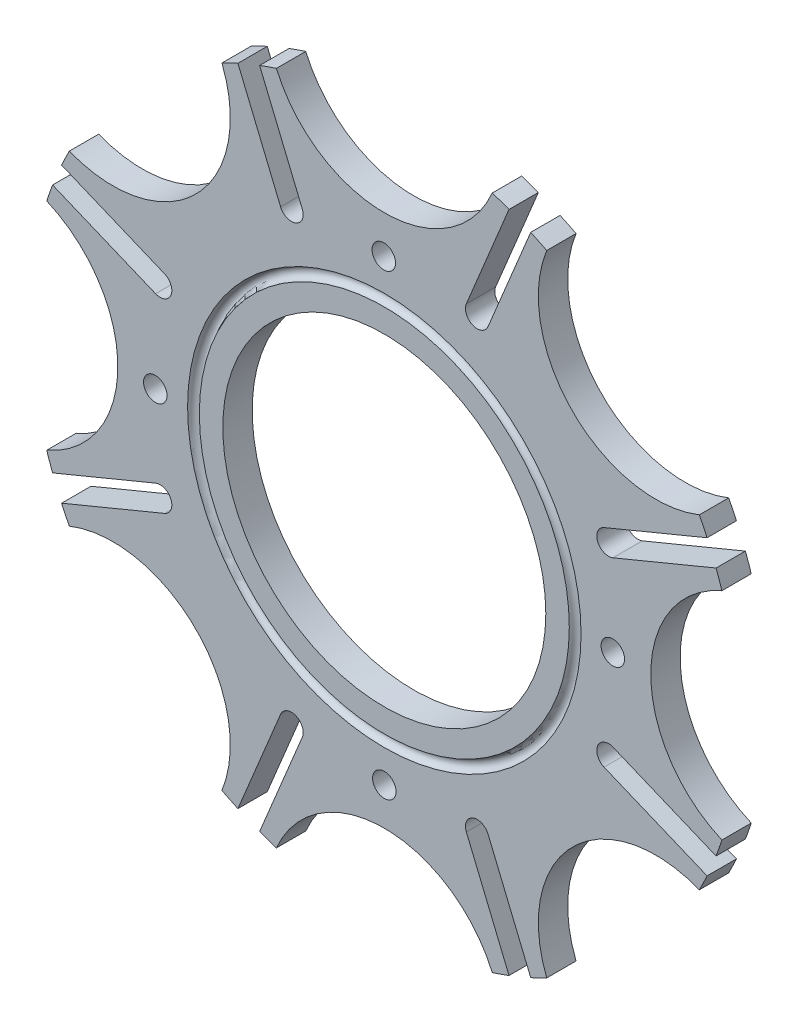
SolidWorks part; units mm, degrees
ref_plane "Front Plane" through (0, 0, 0) normal (0, 0, 1) x (1, 0, 0)
ref_plane "Top Plane" through (0, 0, 0) normal (0, 1, 0) x (1, 0, 0)
ref_plane "Right Plane" through (0, 0, 0) normal (1, 0, 0) x (0, 0, -1)
sketch "Sketch1" plane through (0, 0, 0) normal (0, 0, 1) x (1, 0, 0)
  arc A0 (-42.4681, -112.9795) -> (-36.7553, -114.965) centre (0, 0) ccw
  arc A1 (36.7553, -114.965) -> (42.4681, -112.9795) centre (0, 0) ccw
  arc A2 (49.8591, -109.918) -> (55.3026, -107.2825) centre (0, 0) ccw
  arc A3 (107.2825, -55.3026) -> (109.918, -49.8591) centre (0, 0) ccw
  arc A4 (112.9795, -42.4681) -> (114.965, -36.7553) centre (0, 0) ccw
  arc A5 (114.965, 36.7553) -> (112.9795, 42.4681) centre (0, 0) ccw
  arc A6 (109.918, 49.8591) -> (107.2825, 55.3026) centre (0, 0) ccw
  arc A7 (55.3026, 107.2825) -> (49.8591, 109.918) centre (0, 0) ccw
  arc A8 (42.4681, 112.9795) -> (36.7553, 114.965) centre (0, 0) ccw
  arc A9 (-36.7553, 114.965) -> (-42.4681, 112.9795) centre (0, 0) ccw
  arc A10 (-49.8591, 109.918) -> (-55.3026, 107.2825) centre (0, 0) ccw
  arc A11 (-107.2825, 55.3026) -> (-109.918, 49.8591) centre (0, 0) ccw
  arc A12 (-112.9795, 42.4681) -> (-114.965, 36.7553) centre (0, 0) ccw
  arc A13 (-114.965, -36.7553) -> (-112.9795, -42.4681) centre (0, 0) ccw
  arc A14 (-109.918, -49.8591) -> (-107.2825, -55.3026) centre (0, 0) ccw
  arc A15 (-55.3026, -107.2825) -> (-49.8591, -109.918) centre (0, 0) ccw
  circle A16 centre (0, 0) radius 65 construction
  circle A17 centre (0, 0) radius 62 construction
  circle A18 centre (0, 0) radius 55
  circle A19 centre (0, -0.09) radius 120.7776 construction
  line B0 (0, 0) -> (-46.2257, -111.5988) construction
  line B1 (-27.9356, -77.895) -> (-42.4681, -112.9795)
  line B2 (-35.3266, -74.8336) -> (-49.8591, -109.918)
  line B3 (0, 0) -> (46.2257, -111.5988) construction
  line B4 (35.3266, -74.8336) -> (49.8591, -109.918)
  line B5 (27.9356, -77.895) -> (42.4681, -112.9795)
  line B6 (0, 0) -> (111.5988, -46.2257) construction
  line B7 (77.895, -27.9356) -> (112.9795, -42.4681)
  line B8 (74.8336, -35.3266) -> (109.918, -49.8591)
  line B9 (0, 0) -> (111.5988, 46.2257) construction
  line B10 (74.8336, 35.3266) -> (109.918, 49.8591)
  line B11 (77.895, 27.9356) -> (112.9795, 42.4681)
  line B12 (0, 0) -> (46.2257, 111.5988) construction
  line B13 (27.9356, 77.895) -> (42.4681, 112.9795)
  line B14 (35.3266, 74.8336) -> (49.8591, 109.918)
  line B15 (0, 0) -> (-46.2257, 111.5988) construction
  line B16 (-35.3266, 74.8336) -> (-49.8591, 109.918)
  line B17 (-27.9356, 77.895) -> (-42.4681, 112.9795)
  line B18 (0, 0) -> (-111.5988, 46.2257) construction
  line B19 (-77.895, 27.9356) -> (-112.9795, 42.4681)
  line B20 (-74.8336, 35.3266) -> (-109.918, 49.8591)
  line B21 (0, 0) -> (-111.5988, -46.2257) construction
  line B22 (-74.8336, -35.3266) -> (-109.918, -49.8591)
  line B23 (-77.895, -27.9356) -> (-112.9795, -42.4681)
  arc B24 (-27.9356, -77.895) -> (-35.3266, -74.8336) centre (-31.6311, -76.3643) ccw
  arc B25 (35.3266, -74.8336) -> (27.9356, -77.895) centre (31.6311, -76.3643) ccw
  arc B26 (77.895, -27.9356) -> (74.8336, -35.3266) centre (76.3643, -31.6311) ccw
  arc B27 (74.8336, 35.3266) -> (77.895, 27.9356) centre (76.3643, 31.6311) ccw
  arc B28 (27.9356, 77.895) -> (35.3266, 74.8336) centre (31.6311, 76.3643) ccw
  arc B29 (-35.3266, 74.8336) -> (-27.9356, 77.895) centre (-31.6311, 76.3643) ccw
  arc B30 (-77.895, 27.9356) -> (-74.8336, 35.3266) centre (-76.3643, 31.6311) ccw
  arc B31 (-74.8336, -35.3266) -> (-77.895, -27.9356) centre (-76.3643, -31.6311) ccw
  arc B32 (36.7553, -114.965) -> (-36.7553, -114.965) centre (0, -130.7461) ccw
  arc B33 (107.2825, -55.3026) -> (55.3026, -107.2825) centre (92.4515, -92.4515) ccw
  arc B34 (114.965, 36.7553) -> (114.965, -36.7553) centre (130.7461, 0) ccw
  arc B35 (55.3026, 107.2825) -> (107.2825, 55.3026) centre (92.4515, 92.4515) ccw
  arc B36 (-36.7553, 114.965) -> (36.7553, 114.965) centre (0, 130.7461) ccw
  arc B37 (-107.2825, 55.3026) -> (-55.3026, 107.2825) centre (-92.4515, 92.4515) ccw
  arc B38 (-114.965, -36.7553) -> (-114.965, 36.7553) centre (-130.7461, 0) ccw
  arc B39 (-55.3026, -107.2825) -> (-107.2825, -55.3026) centre (-92.4515, -92.4515) ccw
  line B40 (-78.4, -0.18) -> (-77.6, -0.18)
  line B41 (-78, -0.58) -> (-78, 0.22)
  line B42 (-82.12, -0.18) -> (-78.8, -0.18) construction
  line B43 (-77.2, -0.18) -> (-73.88, -0.18) construction
  line B44 (-78, -4.3) -> (-78, -0.98) construction
  line B45 (-78, 0.62) -> (-78, 3.94) construction
  line B46 (0, -78.4) -> (0, -77.6)
  line B47 (0.4, -78) -> (-0.4, -78)
  line B48 (0, -82.12) -> (0, -78.8) construction
  line B49 (0, -77.2) -> (0, -73.88) construction
  line B50 (4.12, -78) -> (0.8, -78) construction
  line B51 (-0.8, -78) -> (-4.12, -78) construction
  line B52 (78.22, 0) -> (77.42, 0)
  line B53 (77.82, 0.4) -> (77.82, -0.4)
  line B54 (81.94, 0) -> (78.62, 0) construction
  line B55 (77.02, 0) -> (73.7, 0) construction
  line B56 (77.82, 4.12) -> (77.82, 0.8) construction
  line B57 (77.82, -0.8) -> (77.82, -4.12) construction
  line B58 (-0.18, 78.22) -> (-0.18, 77.42)
  line B59 (-0.58, 77.82) -> (0.22, 77.82)
  line B60 (-0.18, 81.94) -> (-0.18, 78.62) construction
  line B61 (-0.18, 77.02) -> (-0.18, 73.7) construction
  line B62 (-4.3, 77.82) -> (-0.98, 77.82) construction
  line B63 (0.62, 77.82) -> (3.94, 77.82) construction
  circle B64 centre (-78, -0.18) radius 4
  circle B65 centre (0, -78) radius 4
  circle B66 centre (77.82, 0) radius 4
  circle B67 centre (-0.18, 77.82) radius 4
  line B68 (-5.5, 0) -> (5.5, 0)
  line B69 (0, -5.5) -> (0, 5.5)
  line B70 (-55.12, 0) -> (-11, 0)
  line B71 (11, 0) -> (55.12, 0)
  line B72 (0, -55.12) -> (0, -11)
  line B73 (0, 11) -> (0, 55.12)
sketch_block_instance "*U1-1"
sketch_block "*U1"
sketch_block_instance "*U3-1"
sketch_block "*U3"
sketch_block_instance "*U5-1"
sketch_block "*U5"
sketch_block_instance "*U7-1"
sketch_block "*U7"
extrude "Boss-Extrude1" add sketch "Sketch1" along normal blind 10 contours B39 A15 B2 B24 B1 A0 B32 A1 B5 B25 B4 A2 B33 A3 B8 B26 B7 A4 B34 A5 B11 B27 B10 A6 B35 A7 B14 B28 B13 A8 B36 A9 B17 B29 B16 A10 B37 A11 B20 B30 B19 A12 B38 A13 B23 B31 B22 A14 B67
sketch "Sketch6" plane through (0, 0, 10) normal (0, 0, -1) x (-1, 0, 0)
  circle A64 centre (0, 0) radius 55 construction
  circle A65 centre (0, 0) radius 55 construction
  circle A66 centre (0, 0) radius 65
  dimension "D1" = 10
sweep "Cut-Sweep1" cut path "Sketch6" circular profile diameter 4 parameters "D3"=4
